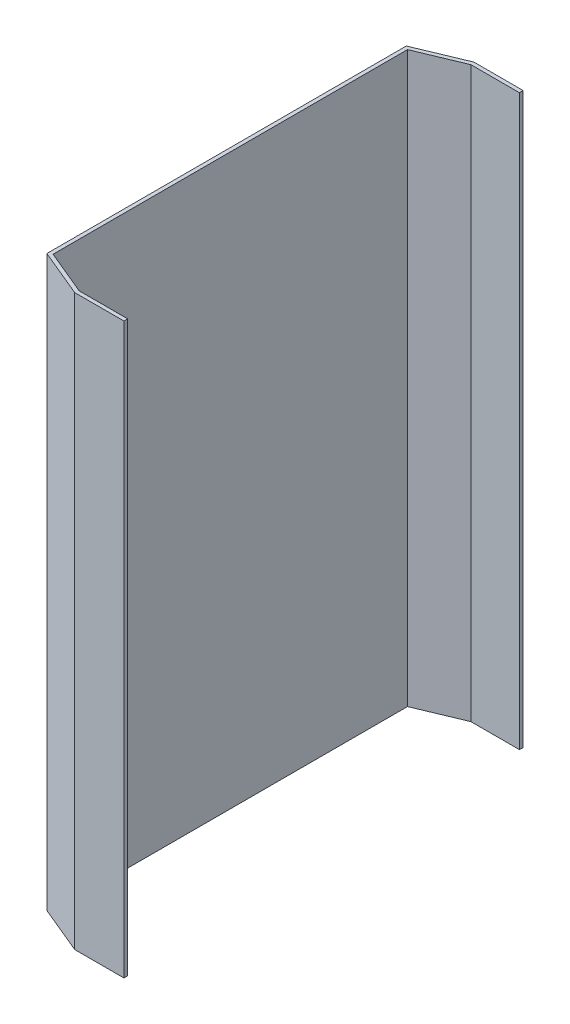
SolidWorks part; units mm, degrees
ref_plane "Plan de face" through (0, 0, 0) normal (0, 0, 1) x (1, 0, 0)
ref_plane "Plan de dessus" through (0, 0, 0) normal (0, 1, 0) x (1, 0, 0)
ref_plane "Plan de droite" through (0, 0, 0) normal (1, 0, 0) x (0, 0, -1)
sketch "Esquisse1" plane through (0, 0, 0) normal (0, 1, 0) x (1, 0, 0)
  line L0 (0, 95) -> (0, -95)
  line L1 (0, 95) -> (24, 105)
  line L2 (24, 105) -> (50, 105)
  line L3 (0, -95) -> (24, -105)
  line L4 (24, -105) -> (50, -105)
  line L5 (23.6, 107) -> (50, 107)
  line L6 (-2, 96.3333) -> (23.6, 107)
  line L7 (-2, 96.3333) -> (-2, -96.3333)
  line L8 (-2, -96.3333) -> (23.6, -107)
  line L9 (23.6, -107) -> (50, -107)
  line L10 (50, 105) -> (50, 107)
  line L11 (50, -107) -> (50, -105)
  dimension "D1" = 190
  dimension "D2" = 24
  dimension "D3" = 10
  dimension "D4" = 10
  dimension "D5" = 24
  dimension "D6" = 26
  dimension "D7" = 26
  dimension "D8" = 26
  dimension "D9" = 26
  dimension "D10" = 0
  dimension "D11" = 95
  dimension "D12" = 2
  dimension "D13" = 2
  dimension "D14" = 2
  dimension "D15" = 2
  dimension "D16" = 2
extrude "Boss.-Extru.1" add sketch "Esquisse1" along normal blind 305
